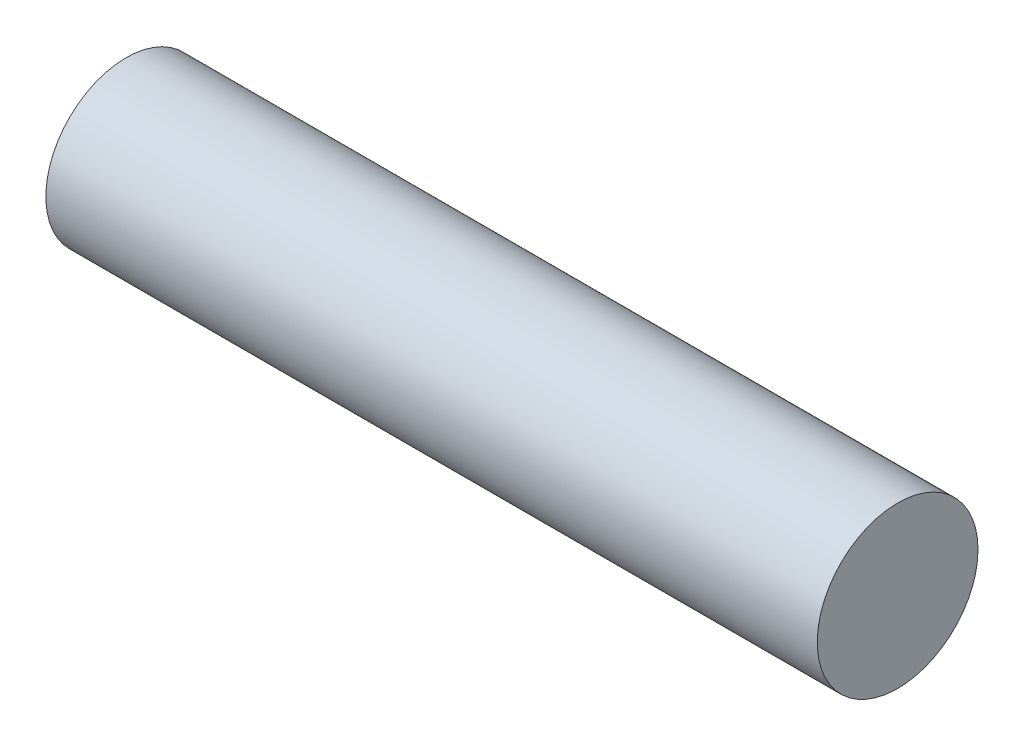
SolidWorks part; units mm, degrees
ref_plane "Ebene vorne" through (0, 0, 0) normal (0, 0, 1) x (1, 0, 0)
ref_plane "Ebene oben" through (0, 0, 0) normal (0, 1, 0) x (1, 0, 0)
ref_plane "Ebene rechts" through (0, 0, 0) normal (1, 0, 0) x (0, 0, -1)
sketch "Sketch1" plane through (0, 0, 0) normal (1, 0, 0) x (0, 0, -1)
  circle A0 centre (0, 0) radius 12.5
  dimension "D1" = 25
extrude "Boss-Extrude1" add sketch "Sketch1" along normal blind 120 contours A0
